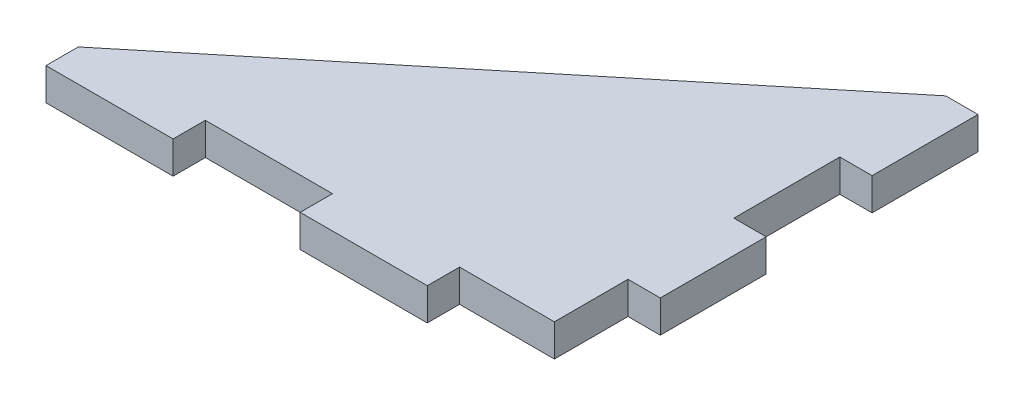
SolidWorks part; units mm, degrees
ref_plane "Front Plane" through (0, 0, 0) normal (0, 0, 1) x (1, 0, 0)
ref_plane "Top Plane" through (0, 0, 0) normal (0, 1, 0) x (1, 0, 0)
ref_plane "Right Plane" through (0, 0, 0) normal (1, 0, 0) x (0, 0, -1)
sketch "Sketch1" plane through (0, 0, 0) normal (0, 1, 0) x (1, 0, 0)
  line L0 (0, 0) -> (24, 0)
  line L1 (96, 20) -> (96, 40)
  line L2 (0, 0) -> (0, 6.096)
  line L3 (96, 80) -> (89.904, 80)
  line L4 (0, 6.096) -> (89.904, 80)
  line L5 (24, 0) -> (24, 6.096)
  line L6 (24, 6.096) -> (48, 6.096)
  line L7 (48, 6.096) -> (48, 0)
  line L8 (72, 0) -> (72, 6.096)
  line L9 (72, 6.096) -> (89.904, 6.096)
  line L10 (24, 6.096) -> (0, 6.096) construction
  line L11 (48, 6.096) -> (72, 6.096) construction
  line L12 (48, 0) -> (72, 0)
  line L13 (96, 60) -> (89.904, 60)
  line L14 (89.904, 60) -> (89.904, 40)
  line L15 (89.904, 40) -> (96, 40)
  line L16 (96, 20) -> (89.904, 20)
  line L17 (89.904, 20) -> (89.904, 6.096)
  line L18 (96, 60) -> (96, 80)
  line L19 (89.904, 60) -> (89.904, 80) construction
  line L20 (89.904, 40) -> (89.904, 20) construction
  line L21 (89.904, 20) -> (89.904, 0) construction
  line L22 (72, 6.096) -> (96, 6.096) construction
  dimension "D1" = 6.096
  dimension "D2" = 96
  dimension "D3" = 80
  dimension "D4" = 20
  dimension "D5" = 24
extrude "Boss-Extrude1" add sketch "Sketch1" along normal blind 6.096
equation "\"mat\"= 6.096"
